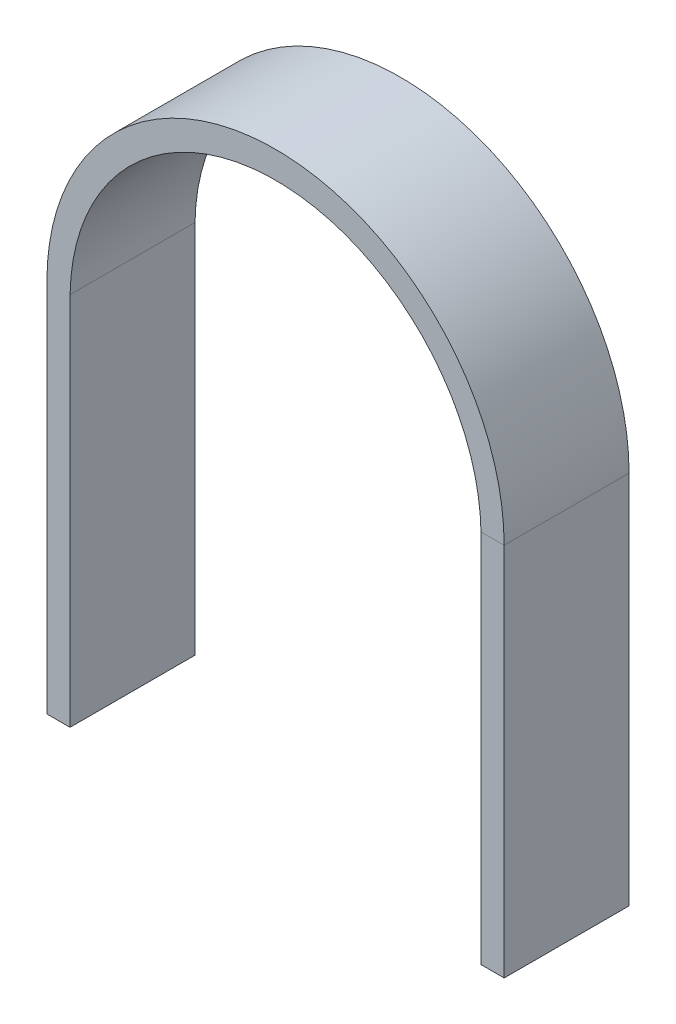
SolidWorks part; units mm, degrees
ref_plane "Front Plane" through (0, 0, 0) normal (0, 0, 1) x (1, 0, 0)
ref_plane "Top Plane" through (0, 0, 0) normal (0, 1, 0) x (1, 0, 0)
ref_plane "Right Plane" through (0, 0, 0) normal (1, 0, 0) x (0, 0, -1)
sketch "Sketch1" plane through (0, 0, 0) normal (0, 1, 0) x (1, 0, 0)
  line L1 (-18.3, 5) -> (18.3, 5)
  line L2 (-18.3, 5) -> (-18.3, -5)
  line L3 (-18.3, -5) -> (18.3, -5)
  line L4 (18.3, 5) -> (18.3, -5)
  line L5 (-18.3, 5) -> (18.3, -5) construction
  line L6 (-18.3, -5) -> (18.3, 5) construction
  point P0 (0, 0)
  dimension "D1" = 10
extrude "Boss-Extrude1" add sketch "Sketch1" along normal blind 30
sketch "Sketch2" plane through (0, 0, 0) normal (0, 1, 0) x (1, 0, 0)
  line L0 (-18.3, -5) -> (18.3, -5) construction
  line L1 (-16.45, 5) -> (16.45, 5)
  line L2 (-16.45, 5) -> (-16.45, -5)
  line L3 (-16.45, -5) -> (16.45, -5)
  line L4 (16.45, 5) -> (16.45, -5)
  line L5 (-16.45, 5) -> (16.45, -5) construction
  line L6 (-16.45, -5) -> (16.45, 5) construction
  point P0 (0, 0)
  dimension "D1" = 32.9
extrude "Cut-Extrude1" cut sketch "Sketch2" along normal through all
sketch "Sketch3" plane through (0, 0, 5) normal (0, 0, 1) x (1, 0, 0)
  line L0 (-18.3, 30) -> (18.3, 30)
  arc A0 (-18.3, 30) -> (18.3, 30) centre (0, 30) cw
extrude "Boss-Extrude3" add sketch "Sketch3" against normal up to surface (10 mm away) up to face at (17.375, 15, -5)
sketch "Sketch4" plane through (0, 0, 5) normal (0, 0, 1) x (1, 0, 0)
  line L0 (-16.45, 29.707) -> (16.45, 29.707)
  arc A0 (-16.45, 29.707) -> (16.45, 29.707) centre (0, 29.707) cw
extrude "Cut-Extrude2" cut sketch "Sketch4" against normal blind 17.038
